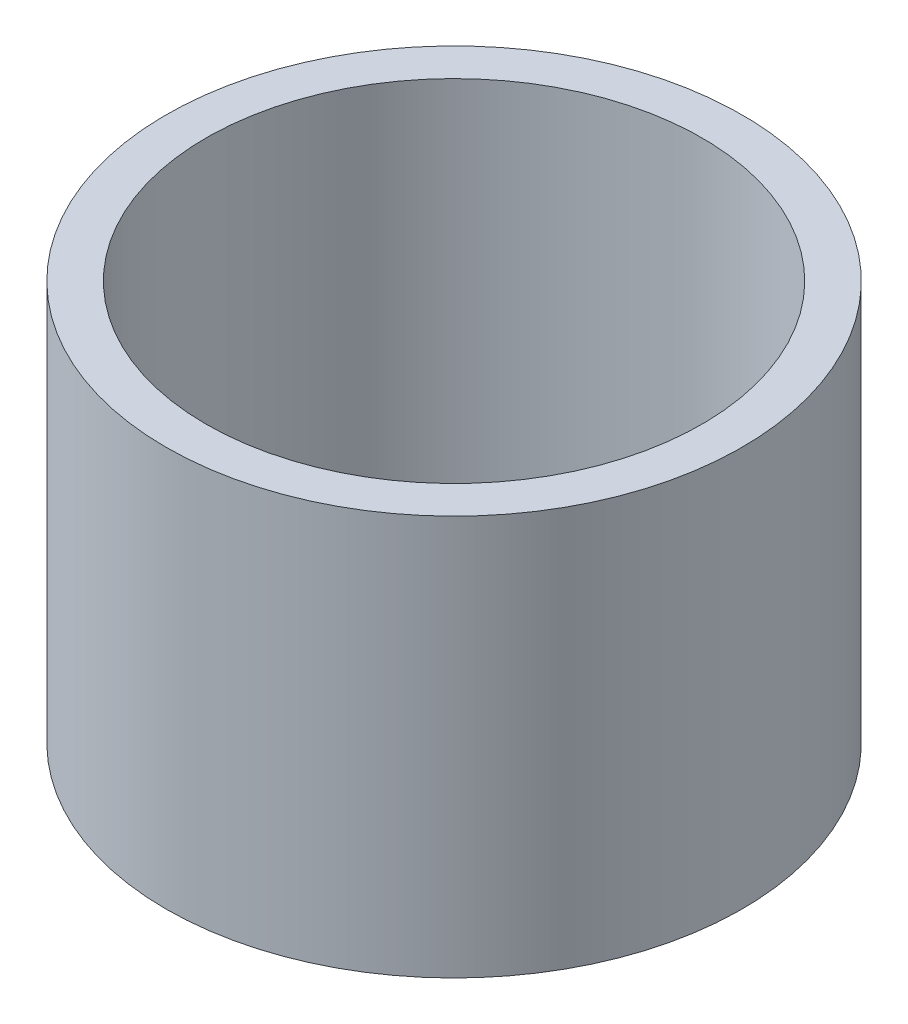
SolidWorks part; units mm, degrees
ref_plane "Front Plane" through (0, 0, 0) normal (0, 0, 1) x (1, 0, 0)
ref_plane "Top Plane" through (0, 0, 0) normal (0, 1, 0) x (1, 0, 0)
ref_plane "Right Plane" through (0, 0, 0) normal (1, 0, 0) x (0, 0, -1)
sketch "Sketch1" plane through (0, 0, 0) normal (0, 1, 0) x (1, 0, 0)
  circle A0 centre (0, 0) radius 3.6
extrude "Boss-Extrude1" add sketch "Sketch1" along normal blind 5
sketch "Sketch2" plane through (0, 5, 0) normal (0, 1, 0) x (1, 0, 0)
  circle A0 centre (0, 0) radius 3.1
extrude "Cut-Extrude1" cut sketch "Sketch2" against normal blind 4.5
